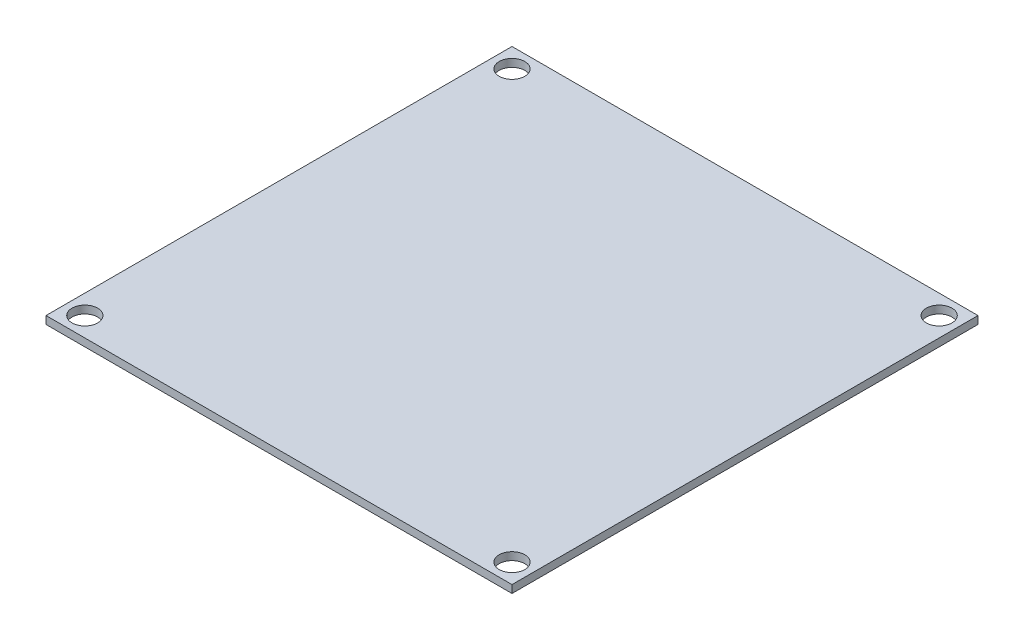
SolidWorks part; units mm, degrees
ref_plane "Alzado" through (0, 0, 0) normal (0, 0, 1) x (1, 0, 0)
ref_plane "Planta" through (0, 0, 0) normal (0, 1, 0) x (1, 0, 0)
ref_plane "Vista lateral" through (0, 0, 0) normal (1, 0, 0) x (0, 0, -1)
sketch "Croquis1" plane through (0, 0, 0) normal (0, 1, 0) x (1, 0, 0)
  line L1 (-30, -30) -> (30, -30)
  line L2 (-30, -30) -> (-30, 30)
  line L3 (-30, 30) -> (30, 30)
  line L4 (30, -30) -> (30, 30)
  line L5 (-30, -30) -> (30, 30) construction
  line L6 (-30, 30) -> (30, -30) construction
  point P0 (0, 0)
  dimension "D1" = 60
  dimension "D2" = 60
extrude "Saliente-Extruir1" add sketch "Croquis1" along normal blind 1
sketch "Croquis3" plane through (0, 1, 0) normal (0, 1, 0) x (1, 0, 0)
  line L0 (0, 0) -> (0, -2.0819)
  line L1 (0, 0) -> (-2.0335, 0)
  line L2 (-30, 30) -> (-30, -30) construction
  line L3 (-30, -30) -> (30, -30) construction
  circle A0 centre (-27.5, -27.5) radius 1.65
  circle A1 centre (27.5, -27.5) radius 1.65
  circle A2 centre (-27.5, 27.5) radius 1.65
  circle A3 centre (27.5, 27.5) radius 1.65
  dimension "D1" = 3.3
  dimension "D2" = 2.5
  dimension "D3" = 2.5
extrude "Cortar-Extruir1" cut sketch "Croquis3" against normal through all contours A2 | A3 | A1 | A0
